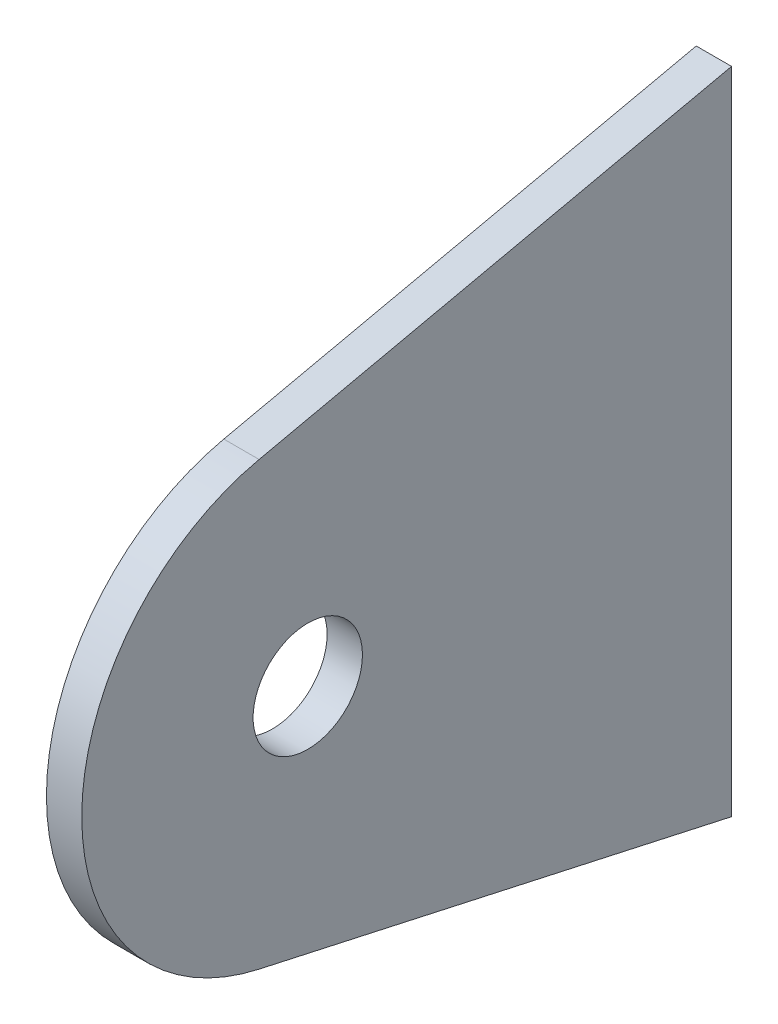
SolidWorks part; units mm, degrees
material "AISI 4130 Steel, annealed at 865C"
ref_plane "X-Y Datum" through (0, 0, 0) normal (0, 0, 1) x (1, 0, 0)
ref_plane "X-Z Datum" through (0, 0, 0) normal (0, 1, 0) x (1, 0, 0)
ref_plane "Y-Z Datum" through (0, 0, 0) normal (1, 0, 0) x (0, 0, -1)
sketch "Sketch1" plane through (0, 0, 0) normal (1, 0, 0) x (0, 0, -1)
  line L0 (-2.1879, 9.9216) -> (19.05, 14.605)
  line L1 (0, 0) -> (19.05, 0) construction
  line L2 (-2.1879, -9.9216) -> (19.05, -14.605)
  line L3 (19.05, -14.605) -> (19.05, 14.605)
  arc A0 (-2.1879, 9.9216) -> (-2.1879, -9.9216) centre (0, 0) ccw
  dimension "D1" = 19.05
  dimension "D2" = 10.16
  dimension "D3" = 29.21
extrude "Boss-Extrude1" add sketch "Sketch1" along normal mid plane 1.5875
hole_wizard "#8 Clearance Hole1" positions "Sketch2" profile "Sketch3" hole size "#8" standard "ANSI Inch" end condition up to next
sketch "Sketch2" plane through (0.7937, 0, 0) normal (1, 0, 0) x (0, 0, -1)
  point P0 (0, 0)
sketch "Sketch3" plane through (0.7937, 0, 0) normal (0, 1, 0) x (0, 0, -1)
  line L0 (0, 0) -> (0, 1.5875)
  line L1 (0, 1.5875) -> (2.4574, 1.5875)
  line L2 (2.4574, 1.5875) -> (2.4574, 0)
  line L5 (2.4574, 0) -> (0, 0)
  line L11 (0, -6.35) -> (0, 107.95) construction
  dimension "Thru Hole Dia." = 4.9149
  dimension "Thru Hole Depth" = 1.5875
